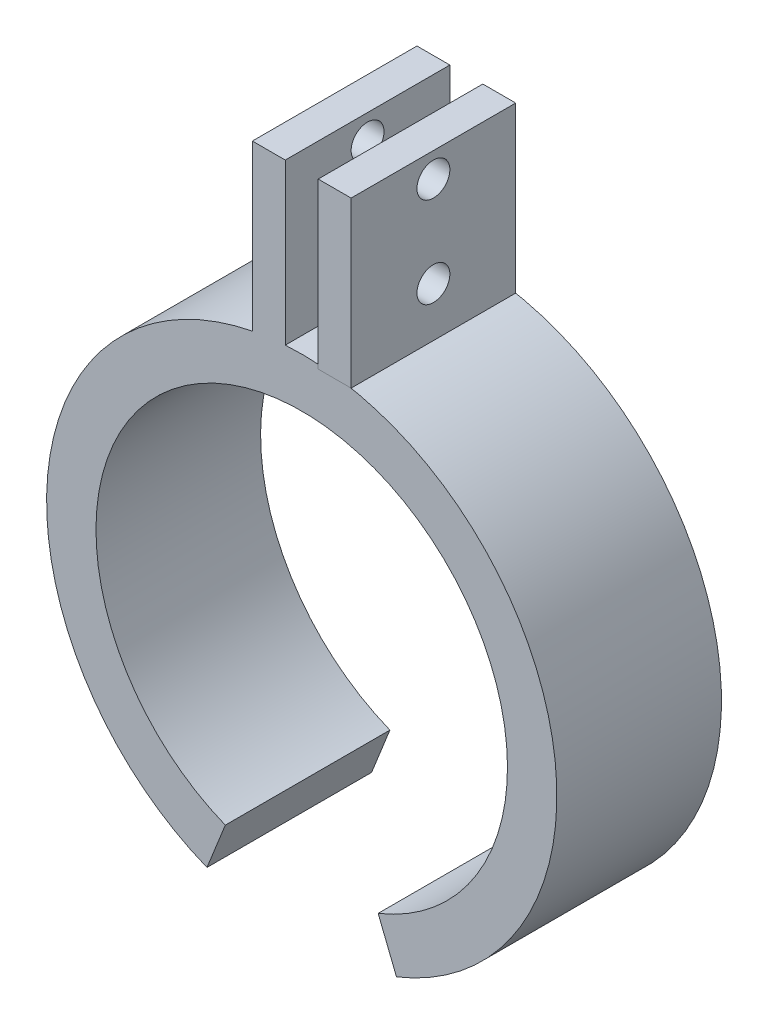
SolidWorks part; units mm, degrees
ref_plane "Front Plane" through (0, 0, 0) normal (0, 0, 1) x (1, 0, 0)
ref_plane "Top Plane" through (0, 0, 0) normal (0, 1, 0) x (1, 0, 0)
ref_plane "Right Plane" through (0, 0, 0) normal (1, 0, 0) x (0, 0, -1)
sketch "Sketch1" plane through (0, 0, 0) normal (0, 0, 1) x (1, 0, 0)
  arc A0 (4.6424, -11.606) -> (-4.6424, -11.606) centre (0, 0) ccw
extrude "Extrude-Thin1" add sketch "Sketch1" along normal blind 10 thin
sketch "Sketch3" plane through (0, 0, 10) normal (0, 0, 1) x (1, 0, 0)
  line L0 (-3, 15.2069) -> (-3, 25.2069)
  line L1 (3, 15.2069) -> (3, 23.1766)
  arc A0 (5.7566, -14.3914) -> (-5.7566, -14.3914) centre (0, 0) ccw construction
  dimension "D1" = 10
  dimension "D3" = 3
  dimension "D4" = 3
extrude "Extrude-Thin2" add sketch "Sketch3" against normal blind 10 thin contours L0
sketch "Sketch4" plane through (0, 0, 0) normal (0, 0, 1) x (1, 0, 0)
  line L1 (3, 15.2069) -> (3, 25.2069)
  arc A0 (5.7566, -14.3914) -> (-1, 15.4677) centre (0, 0) ccw construction
  point P0 (3.4046, 14.6085)
  dimension "D1" = 3
  dimension "D2" = 10
extrude "Extrude-Thin3" add sketch "Sketch4" along normal blind 10 separate body thin contours L1 thin type one direction reverse wall 2
sketch "Sketch5" plane through (-3, 0, 0) normal (-1, 0, 0) x (0, 0, 1)
  line L0 (0, 15.2069) -> (10, 15.2069) construction
  line L1 (10, 15.2069) -> (10, 25.2069) construction
  circle A0 centre (5, 23.7069) radius 1
  circle A1 centre (5, 18.2069) radius 1
  dimension "D3" = 5
  dimension "D1" = 3
  dimension "D2" = 8.5
  dimension "D4" = 5
extrude "Cut-Extrude1" cut sketch "Sketch5" against normal through all both and the other way through all
